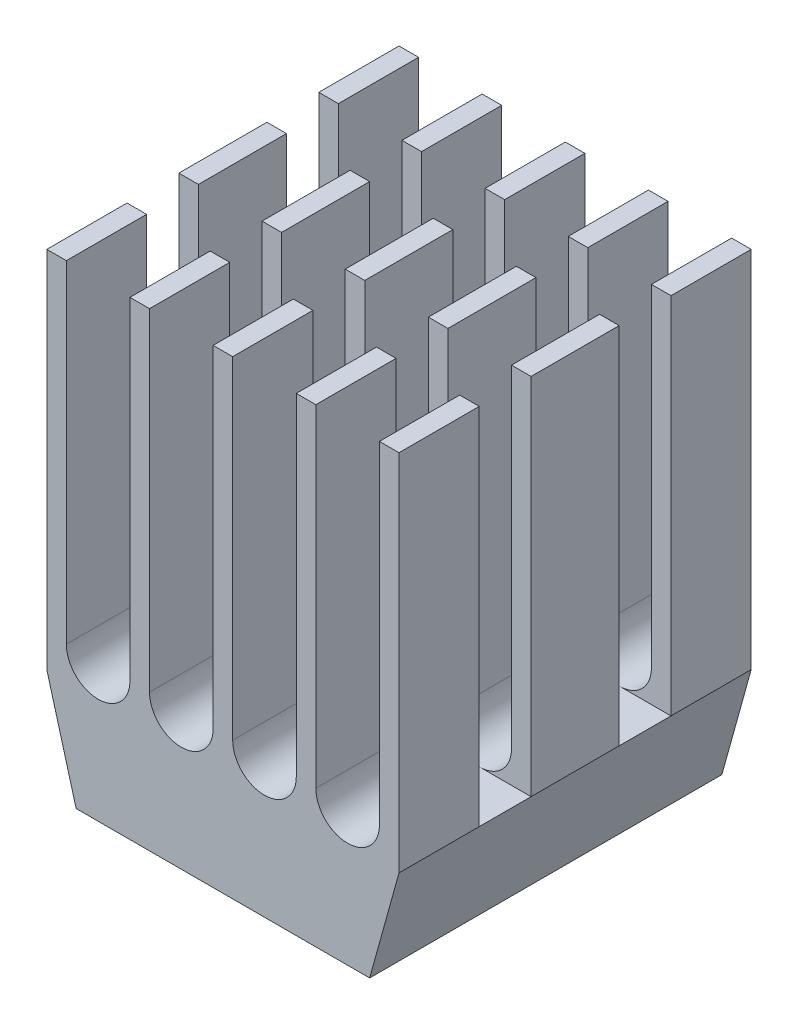
SolidWorks part; units mm, degrees
ref_plane "Ebene vorne" through (0, 0, 0) normal (0, 0, 1) x (1, 0, 0)
ref_plane "Ebene oben" through (0, 0, 0) normal (0, 1, 0) x (1, 0, 0)
ref_plane "Ebene rechts" through (0, 0, 0) normal (1, 0, 0) x (0, 0, -1)
sketch "Skizze1" plane through (0, 0, 0) normal (0, 0, 1) x (1, 0, 0)
  line L0 (-4.5, 12) -> (-4.5, 2.7)
  line L1 (-4.5, 2.7) -> (-3.75, 0)
  line L2 (-3.75, 0) -> (3.75, 0)
  line L3 (3.75, 0) -> (4.5, 2.7)
  line L4 (4.5, 2.7) -> (4.5, 12)
  line L5 (4.5, 12) -> (-4.5, 12)
  line L6 (0, -1000) -> (0, 49000) construction
  dimension "D1" = 9
  dimension "D2" = 7.5
  dimension "D3" = 2.7
  dimension "D4" = 12
extrude "Aufsatz-Linear austragen1" add sketch "Skizze1" along normal mid plane 9
sketch "Skizze2" plane through (0, 0, 4.5) normal (0, 0, 1) x (1, 0, 0)
  line L0 (-3.1875, 12) -> (-3.1875, 3.5125) construction
  line L1 (-2.375, 12) -> (-2.375, 3.5125)
  line L2 (-4, 12) -> (-4, 3.5125)
  line L3 (-4.5, 12) -> (-4.5, 2.7) construction
  line L4 (4.5, 12) -> (-4.5, 12) construction
  line L5 (-4.5, 2.7) -> (4.5, 2.7) construction
  line L6 (-1.0625, 12) -> (-1.0625, 3.5125) construction
  line L7 (-0.25, 12) -> (-0.25, 3.5125)
  line L8 (-1.875, 12) -> (-1.875, 3.5125)
  line L9 (1.0625, 12) -> (1.0625, 3.5125) construction
  line L10 (1.875, 12) -> (1.875, 3.5125)
  line L11 (0.25, 12) -> (0.25, 3.5125)
  line L12 (3.1875, 12) -> (3.1875, 3.5125) construction
  line L13 (4, 12) -> (4, 3.5125)
  line L14 (2.375, 12) -> (2.375, 3.5125)
  line L15 (4.5, 2.7) -> (4.5, 12) construction
  arc A0 (-2.375, 12) -> (-4, 12) centre (-3.1875, 12) ccw
  arc A1 (-4, 3.5125) -> (-2.375, 3.5125) centre (-3.1875, 3.5125) ccw
  arc A2 (-0.25, 12) -> (-1.875, 12) centre (-1.0625, 12) ccw
  arc A3 (-1.875, 3.5125) -> (-0.25, 3.5125) centre (-1.0625, 3.5125) ccw
  arc A4 (1.875, 12) -> (0.25, 12) centre (1.0625, 12) ccw
  arc A5 (0.25, 3.5125) -> (1.875, 3.5125) centre (1.0625, 3.5125) ccw
  arc A6 (4, 12) -> (2.375, 12) centre (3.1875, 12) ccw
  arc A7 (2.375, 3.5125) -> (4, 3.5125) centre (3.1875, 3.5125) ccw
  point P2 (-3.1875, 7.7563)
  point P18 (-1.0625, 7.7563)
  point P25 (1.0625, 7.7563)
  point P32 (3.1875, 7.7563)
  dimension "D1" = 0.5
  dimension "D3" = 0.5
  dimension "D4" = 0.5
  dimension "D2" = 4
extrude "Schnitt-Linear austragen1" cut sketch "Skizze2" against normal up to surface (9 mm away) up to face at (0, 4.9, -4.5)
sketch "Skizze3" plane through (4.5, 0, 0) normal (1, 0, 0) x (0, 0, -1)
  line L0 (-4.5, 12) -> (4.5, 12) construction
  line L1 (-2.45, 12) -> (-1.125, 12)
  line L2 (-2.45, 12) -> (-2.45, 2.7)
  line L3 (-2.45, 2.7) -> (-1.125, 2.7)
  line L4 (-1.125, 12) -> (-1.125, 2.7)
  line L5 (-4.5, 2.7) -> (4.5, 2.7) construction
  line L6 (1.125, 12) -> (1.125, 2.7)
  line L7 (1.125, 12) -> (2.45, 12)
  line L8 (2.45, 12) -> (2.45, 2.7)
  line L9 (1.125, 2.7) -> (2.45, 2.7)
  line L10 (0, -1000) -> (0, 49000) construction
  line L11 (-4.5, 2.7) -> (-4.5, 12) construction
  dimension "D2" = 2.05
  dimension "D3" = 2.25
  dimension "D1" = 2
extrude "Schnitt-Linear austragen2" cut sketch "Skizze3" against normal up to surface (9 mm away) up to face at (-4.5, 7.35, 0)
sketch "Skizze4" plane through (0, 0, 0) normal (0, -1, 0) x (1, 0, 0)
  line L0 (-3.75, 4.5) -> (3.75, 4.5) construction
  line L1 (-3.65, -4.4) -> (3.65, -4.4)
  line L2 (-3.65, -4.4) -> (-3.65, 4.4)
  line L3 (-3.65, 4.4) -> (3.65, 4.4)
  line L4 (3.65, -4.4) -> (3.65, 4.4)
  line L5 (-3.65, -4.4) -> (3.65, 4.4) construction
  line L6 (-3.65, 4.4) -> (3.65, -4.4) construction
  line L7 (-3.75, 4.5) -> (-3.75, -4.5) construction
  point P0 (0, 0)
  dimension "D1" = 0.1
  dimension "D2" = 0.1
extrude "Aufsatz-Linear austragen2" add sketch "Skizze4" along normal blind 0.1
